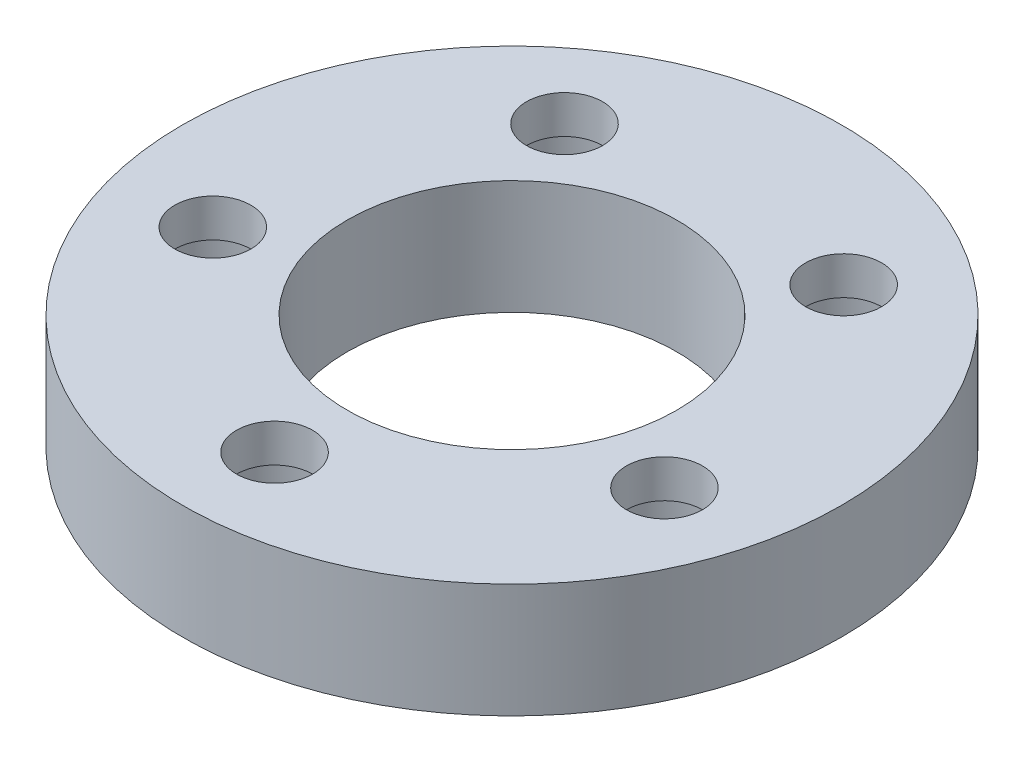
SolidWorks part; units mm, degrees
ref_plane "Front Plane" through (0, 0, 0) normal (0, 0, 1) x (1, 0, 0)
ref_plane "Top Plane" through (0, 0, 0) normal (0, 1, 0) x (1, 0, 0)
ref_plane "Right Plane" through (0, 0, 0) normal (1, 0, 0) x (0, 0, -1)
sketch "Sketch1" plane through (0, 0, 0) normal (0, 0, 1) x (1, 0, 0)
  line L0 (22, -25.3372) -> (11, -25.3372)
  line L2 (0, 18.6628) -> (0, 5.4128)
  line L3 (22, -25.3372) -> (11, -25.3372)
  line L4 (22, -25.3372) -> (22, -32.9572)
  line L5 (11, -18.3372) -> (11, -25.3372)
  line L6 (22, -32.9572) -> (11, -32.9572)
  line L7 (11, -25.3372) -> (11, -32.9572)
  ellipse E1 centre (11, -25.3372) end of major axis (0, -25.3372) minor radius 7 (11, -18.3372) -> (22, -25.3372) cw
  dimension "D1" = 7.62
revolve "Revolve1" add sketch "Sketch1" angle 360 about L2
sketch "Sketch2" plane through (0, -32.9572, 0) normal (0, -1, 0) x (1, 0, 0)
  circle A0 centre (15.0742, 4.8979) radius 2.54
  circle A1 centre (0, 15.85) radius 2.54
  circle A2 centre (9.3164, -12.8229) radius 2.54
  circle A3 centre (-9.3164, -12.8229) radius 2.54
  circle A4 centre (-15.0742, 4.8979) radius 2.54
  point P0 (0, 0)
  point P16 (0, 0)
  dimension "D1" = 15.85
  dimension "D2" = 5
extrude "Cut-Extrude1" cut sketch "Sketch2" against normal through all
sketch "Sketch3" plane through (0, -32.9572, 0) normal (0, -1, 0) x (-1, 0, 0)
  circle A0 centre (0, -15.85) radius 3.9688
  circle A1 centre (-15.0742, -4.8979) radius 3.9688
  circle A2 centre (-9.3164, 12.8229) radius 3.9687
  circle A3 centre (9.3164, 12.8229) radius 3.9687
  circle A4 centre (15.0742, -4.8979) radius 3.9688
  point P13 (0, 0)
  dimension "D1" = 7.9375
  dimension "D2" = 5
extrude "Cut-Extrude2" cut sketch "Sketch3" against normal blind 5.08
